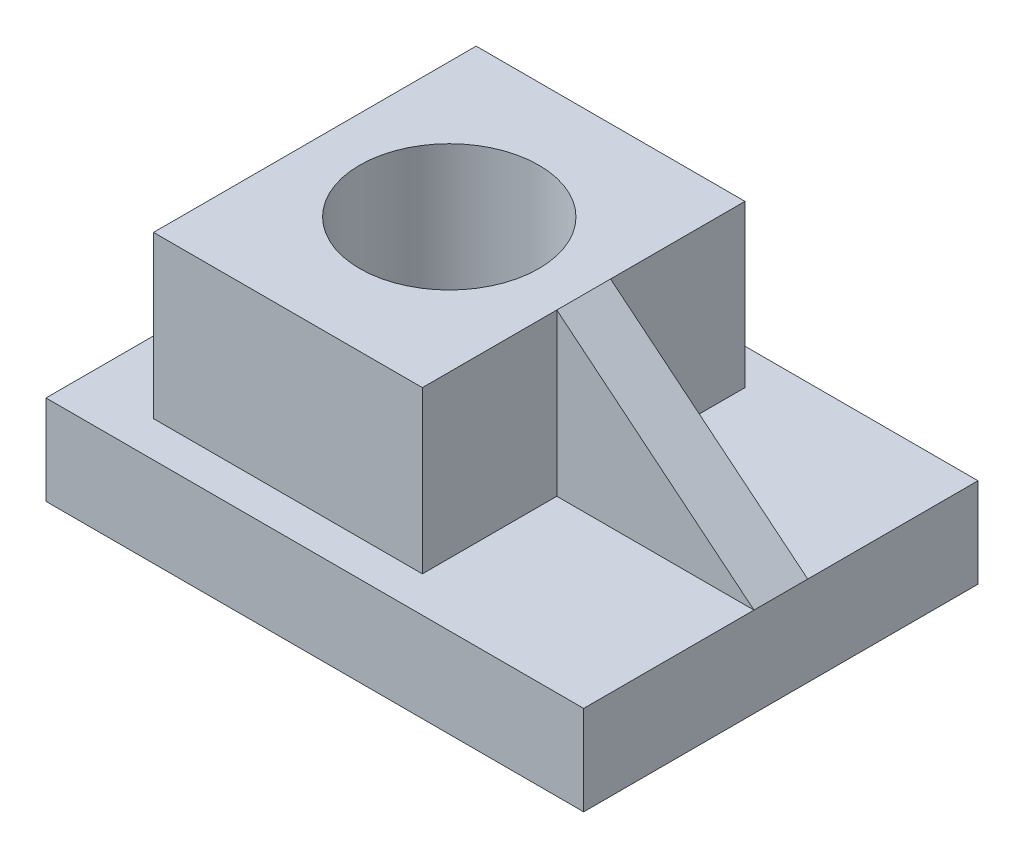
SolidWorks part; units mm, degrees
ref_plane "前视基准面" through (0, 0, 0) normal (0, 0, 1) x (1, 0, 0)
ref_plane "上视基准面" through (0, 0, 0) normal (0, 1, 0) x (1, 0, 0)
ref_plane "右视基准面" through (0, 0, 0) normal (1, 0, 0) x (0, 0, -1)
other "Configuration Table"
sketch "草图1" plane through (0, 0, 0) normal (0, 1, 0) x (1, 0, 0)
  line L1 (-30, -22) -> (30, -22)
  line L6 (-30, -22) -> (-30, 22)
  line L7 (-30, 22) -> (30, 22)
  line L8 (30, -22) -> (30, 22)
  line L9 (-30, -22) -> (30, 22) construction
  line L10 (-30, 22) -> (30, -22) construction
  point P0 (0, 0)
  dimension "D1" = 60
  dimension "D2" = 44
extrude "凸台-拉伸1" add sketch "草图1" along normal blind 10
sketch "草图2" plane through (0, 10, 0) normal (0, 1, 0) x (1, 0, 0)
  line L0 (-30, 22) -> (-30, -22) construction
  line L1 (-22, -18) -> (8, -18)
  line L2 (-22, -18) -> (-22, 18)
  line L3 (-22, 18) -> (8, 18)
  line L4 (8, -18) -> (8, 18)
  line L5 (-22, -18) -> (8, 18) construction
  line L6 (-22, 18) -> (8, -18) construction
  line L7 (-1000, 0) -> (49000, 0) construction
  point P0 (-7, 0)
  dimension "D1" = 36
  dimension "D2" = 30
  dimension "D3" = 23
extrude "凸台-拉伸2" add sketch "草图2" along normal blind 18
sketch "草图3" plane through (0, 28, 0) normal (0, 1, 0) x (1, 0, 0)
  line L0 (-22, 18) -> (8, -18) construction
  circle A0 centre (-7, 0) radius 10
  dimension "D1" = 20
extrude "切除-拉伸1" cut sketch "草图3" against normal through all
sketch "草图4" plane through (0, 10, 0) normal (0, 1, 0) x (1, 0, 0)
  line L0 (8, 0) -> (30, 0) construction
  line L1 (8, -18) -> (8, 18) construction
  line L2 (30, -22) -> (30, 22) construction
ref_plane "基准面1" through (0, 0, 0) normal (0, 0, 1) x (1, 0, 0)
sketch "草图5" plane through (0, 0, 0) normal (0, 0, 1) x (1, 0, 0)
  line L0 (8, 28) -> (30, 10)
rib "筋1" sketch "草图5" sketch "草图5" thickness 6 extrusion direction parallel to sketch draft on no parameters "D1"=6
